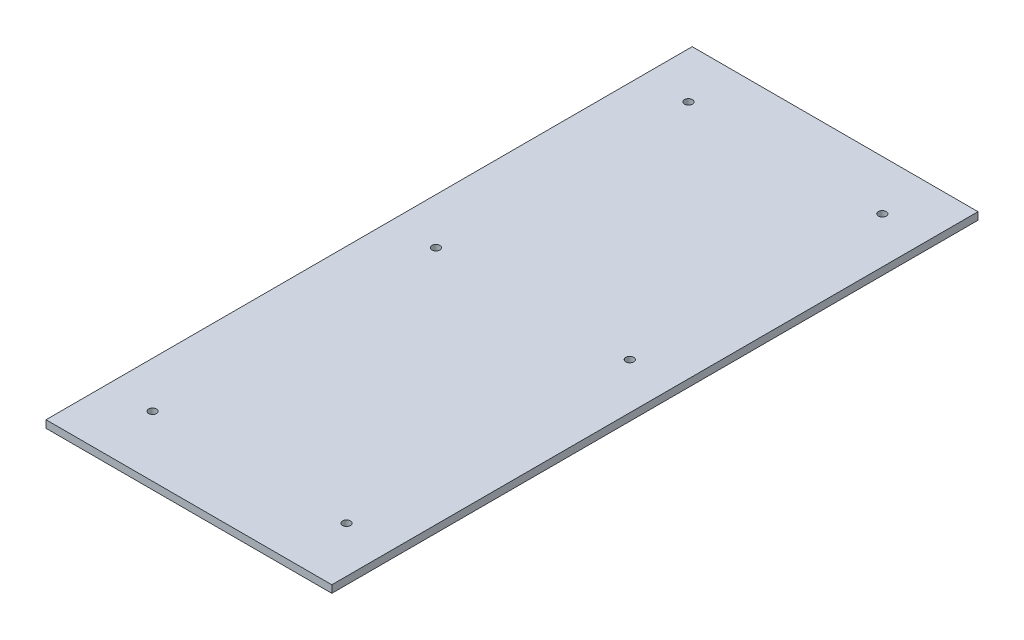
SolidWorks part; units mm, degrees
ref_plane "Plan de face" through (0, 0, 0) normal (0, 0, 1) x (1, 0, 0)
ref_plane "Plan de dessus" through (0, 0, 0) normal (0, 1, 0) x (1, 0, 0)
ref_plane "Plan de droite" through (0, 0, 0) normal (1, 0, 0) x (0, 0, -1)
sketch "Esquisse1" plane through (0, 0, 0) normal (0, 1, 0) x (1, 0, 0)
  line L1 (-34.9255, 37.0612) -> (80.0745, 37.0612)
  line L2 (-34.9255, 37.0612) -> (-34.9255, -222.9388)
  line L3 (-34.9255, -222.9388) -> (80.0745, -222.9388)
  line L4 (80.0745, 37.0612) -> (80.0745, -222.9388)
  dimension "D1" = 115
  dimension "D2" = 260
extrude "Boss.-Extru.1" add sketch "Esquisse1" along normal blind 3 contours L1 L4 L3 L2
sketch "Esquisse2" plane through (0, 3, 0) normal (0, 1, 0) x (1, 0, 0)
  line L0 (-34.9255, -222.9388) -> (80.0745, -222.9388) construction
  line L2 (-34.9255, 37.0612) -> (-34.9255, -222.9388) construction
  line L3 (-34.9255, 37.0612) -> (80.0745, 37.0612) construction
  circle A0 centre (-16.4255, -198.5388) radius 1.6
  circle A1 centre (61.5745, -198.5388) radius 1.6
  circle A2 centre (-16.4255, -84.5388) radius 1.6
  circle A3 centre (61.5745, -84.5388) radius 1.6
  circle A4 centre (-16.4255, 17.0612) radius 1.6
  circle A5 centre (61.5745, 17.0612) radius 1.6
  dimension "D3" = 3.2
  dimension "D4" = 3.2
  dimension "D9" = 3.2
  dimension "D10" = 3.2
  dimension "D17" = 3.2
  dimension "D18" = 3.2
  dimension "D1" = 24.4
  dimension "D2" = 24.4
  dimension "D5" = 78
  dimension "D6" = 18.5
  dimension "D7" = 114
  dimension "D8" = 114
  dimension "D11" = 78
  dimension "D12" = 18.5
  dimension "D13" = 20
  dimension "D14" = 20
  dimension "D15" = 78
  dimension "D16" = 18.5
extrude "Enlèv. mat.-Extru.1" cut sketch "Esquisse2" against normal up to next
equation "\"D1@Esquisse2\"=10.4+14"
equation "\"D5@Esquisse2\"=100-22"
equation "\"D6@Esquisse2\"=(115-78)/2"
equation "\"D7@Esquisse2\"=142-14-14"
equation "\"D13@Esquisse2\"=6+14"
